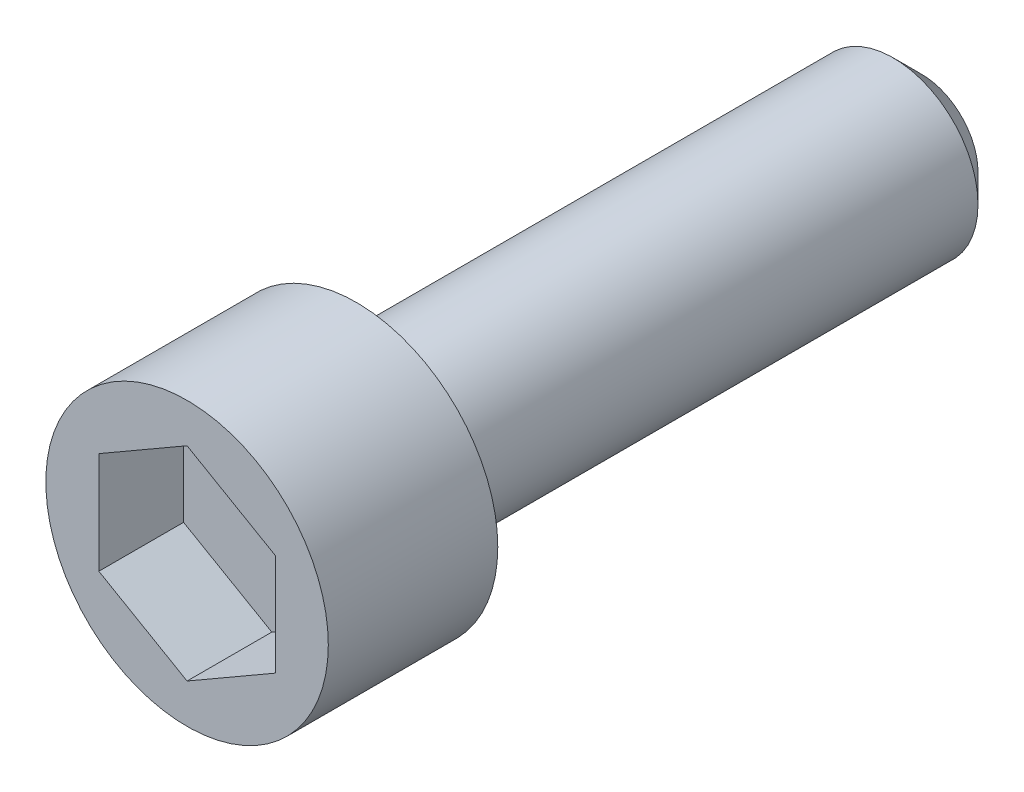
SolidWorks part; units mm, degrees
ref_plane "前视基准面" through (0, 0, 0) normal (0, 0, 1) x (1, 0, 0)
ref_plane "上视基准面" through (0, 0, 0) normal (0, 1, 0) x (1, 0, 0)
ref_plane "右视基准面" through (0, 0, 0) normal (1, 0, 0) x (0, 0, -1)
sketch "草图1" plane through (0, 0, 0) normal (0, 0, 1) x (1, 0, 0)
  circle A0 centre (0, 0) radius 1.5
extrude "凸台-拉伸1" add sketch "草图1" along normal blind 10
sketch "草图2" plane through (0, 0, 10) normal (0, 0, 1) x (1, 0, 0)
  circle A0 centre (0, 0) radius 2.5
extrude "凸台-拉伸2" add sketch "草图2" along normal blind 3
sketch "草图3" plane through (0, 0, 13) normal (0, 0, 1) x (1, 0, 0)
  line L1 (0, 1.8034) -> (-1.5618, 0.9017)
  line L2 (-1.5618, 0.9017) -> (-1.5618, -0.9017)
  line L3 (-1.5618, -0.9017) -> (0, -1.8034)
  line L4 (0, -1.8034) -> (1.5618, -0.9017)
  line L5 (1.5618, -0.9017) -> (1.5618, 0.9017)
  line L6 (1.5618, 0.9017) -> (0, 1.8034)
  circle A0 centre (0, 0) radius 1.5618 construction
extrude "切除-拉伸1" cut sketch "草图3" against normal blind 1.5
chamfer "倒角1" distance 0.5 angle 45 1 edges at (1.5, 0, 0)
